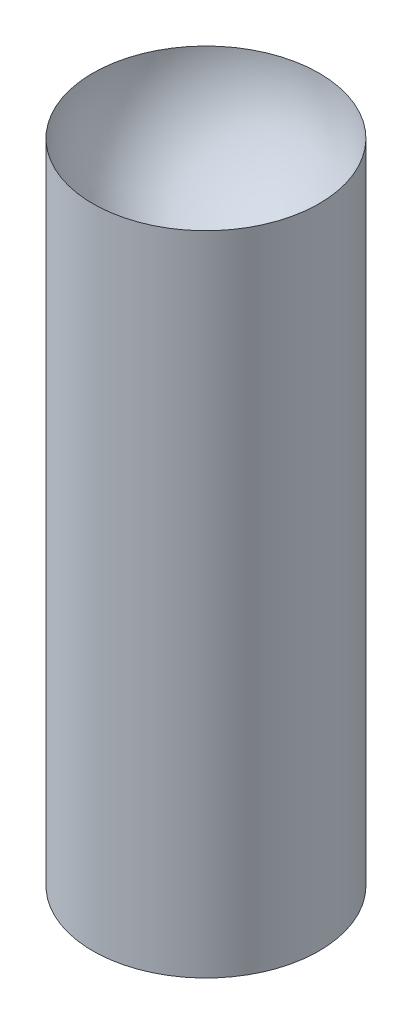
SolidWorks part; units mm, degrees
ref_plane "Front Plane" through (0, 0, 0) normal (0, 0, 1) x (1, 0, 0)
ref_plane "Top Plane" through (0, 0, 0) normal (0, 1, 0) x (1, 0, 0)
ref_plane "Right Plane" through (0, 0, 0) normal (1, 0, 0) x (0, 0, -1)
sketch "Sketch2" plane through (0, 0, 0) normal (1, 0, 0) x (0, 0, -1)
  line L0 (0, 0) -> (2.5, 0)
  line L1 (2.5, 0) -> (2.5, 14.3)
  line L2 (0, 0) -> (0, 11.8)
  arc A0 (2.5, 14.3) -> (0, 11.8) centre (0, 14.3) cw
  dimension "D3" = 2.5
  dimension "D1" = 14.3
  dimension "D2" = 2.5
revolve "Revolve1" add sketch "Sketch2" angle 360 about L2
